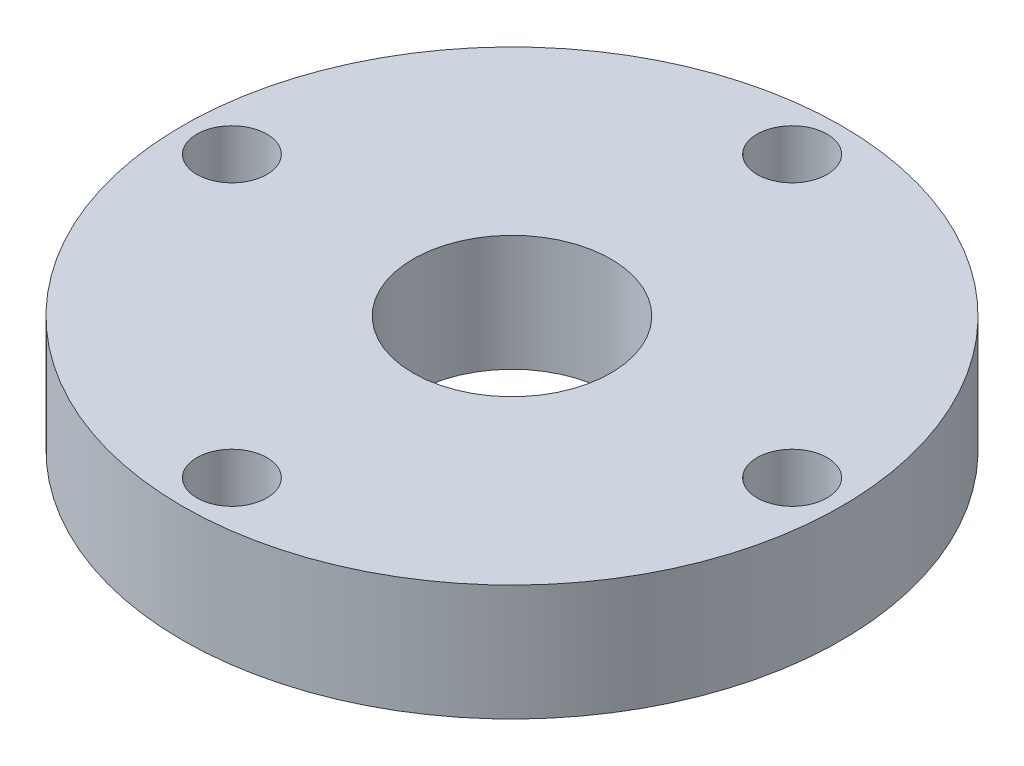
SolidWorks part; units mm, degrees
ref_plane "Front Plane" through (0, 0, 0) normal (1, 0, 0) x (0, 1, 0)
ref_plane "Top Plane" through (0, 0, 0) normal (0, 0, 1) x (0, 1, 0)
ref_plane "Right Plane" through (0, 0, 0) normal (0, 1, 0) x (-1, 0, 0)
sketch "Sketch1" plane through (0, 0, 0) normal (0, 0, 1) x (0, 1, 0)
  line L0 (-11.176, 0) -> (-11.176, 63.5)
  line L1 (-11.176, 63.5) -> (11.176, 63.5)
  line L2 (11.176, 63.5) -> (11.176, 0)
  line L3 (11.176, 0) -> (-11.176, 0)
  line L4 (-36.576, 0) -> (36.576, 0) construction
revolve "Revolve1" add sketch "Sketch1" angle 360 about L4
sketch "Sketch2" plane through (0, 0, 0) normal (0, 1, 0) x (-1, 0, 0)
  circle A0 centre (0, 0) radius 19.05
extrude "Cut-Extrude2" cut sketch "Sketch2" against normal up to next from offset 11.176
sketch "Sketch3" plane through (0, 0, 0) normal (0, 1, 0) x (-1, 0, 0)
  circle A0 centre (53.975, 0) radius 4.3688
extrude "Cut-Extrude4" cut sketch "Sketch3" against normal blind 127 from offset 11.176
sketch "Sketch4" plane through (0, 0, 0) normal (0, 1, 0) x (-1, 0, 0)
  circle A0 centre (53.975, 0) radius 6.7437
extrude "Cut-Extrude6" cut sketch "Sketch4" against normal blind 9.652 from offset 11.176
sketch "Sketch5" plane through (0, 0, 0) normal (0, 1, 0) x (-1, 0, 0)
  circle A0 centre (0, 53.975) radius 4.3688
  circle A1 centre (-53.975, 0) radius 4.3688
  circle A2 centre (0, -53.975) radius 4.3688
extrude "Cut-Extrude8" cut sketch "Sketch5" against normal blind 127 from offset 11.176
sketch "Sketch6" plane through (0, 0, 0) normal (0, 1, 0) x (-1, 0, 0)
  circle A0 centre (0, 53.975) radius 6.7437
  circle A1 centre (-53.975, 0) radius 6.7437
  circle A2 centre (0, -53.975) radius 6.7437
extrude "Cut-Extrude10" cut sketch "Sketch6" against normal blind 9.652 from offset 11.176
